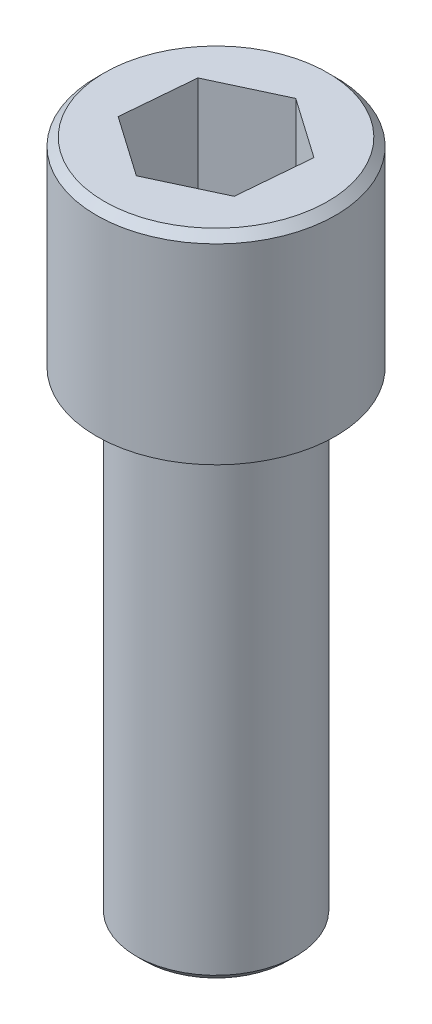
SolidWorks part; units mm, degrees
ref_plane "Přední rovina" through (0, 0, 0) normal (0, 0, 1) x (1, 0, 0)
ref_plane "Horní rovina" through (0, 0, 0) normal (0, 1, 0) x (1, 0, 0)
ref_plane "Pravá rovina" through (0, 0, 0) normal (1, 0, 0) x (0, 0, -1)
sketch "Skica1" plane through (0, 0, 0) normal (0, 1, 0) x (1, 0, 0)
  circle A0 centre (0, 0) radius 2.5
  dimension "D1" = 5
extrude "Přidat vysunutím1" add sketch "Skica1" along normal blind 15
sketch "Skica2" plane through (0, 15, 0) normal (0, 1, 0) x (1, 0, 0)
  circle A0 centre (0, 0) radius 3.75
  dimension "D1" = 7.5
extrude "Přidat vysunutím2" add sketch "Skica2" along normal blind 6.25
sketch "Skica3" plane through (0, 21.25, 0) normal (0, 1, 0) x (1, 0, 0)
  line L1 (-0.1991, -2.3008) -> (1.893, -1.3228)
  line L2 (1.893, -1.3228) -> (2.0921, 0.978)
  line L3 (2.0921, 0.978) -> (0.1991, 2.3008)
  line L4 (0.1991, 2.3008) -> (-1.893, 1.3228)
  line L5 (-1.893, 1.3228) -> (-2.0921, -0.978)
  line L6 (-2.0921, -0.978) -> (-0.1991, -2.3008)
  circle A0 centre (0, 0) radius 2 construction
  dimension "D1" = 4
extrude "Odebrat vysunutím1" cut sketch "Skica3" against normal blind 3.75
chamfer "Zkosení1" distance 0.25 angle 45 2 edges at (0, 0, 2.5) (0, 21.25, 3.75)
